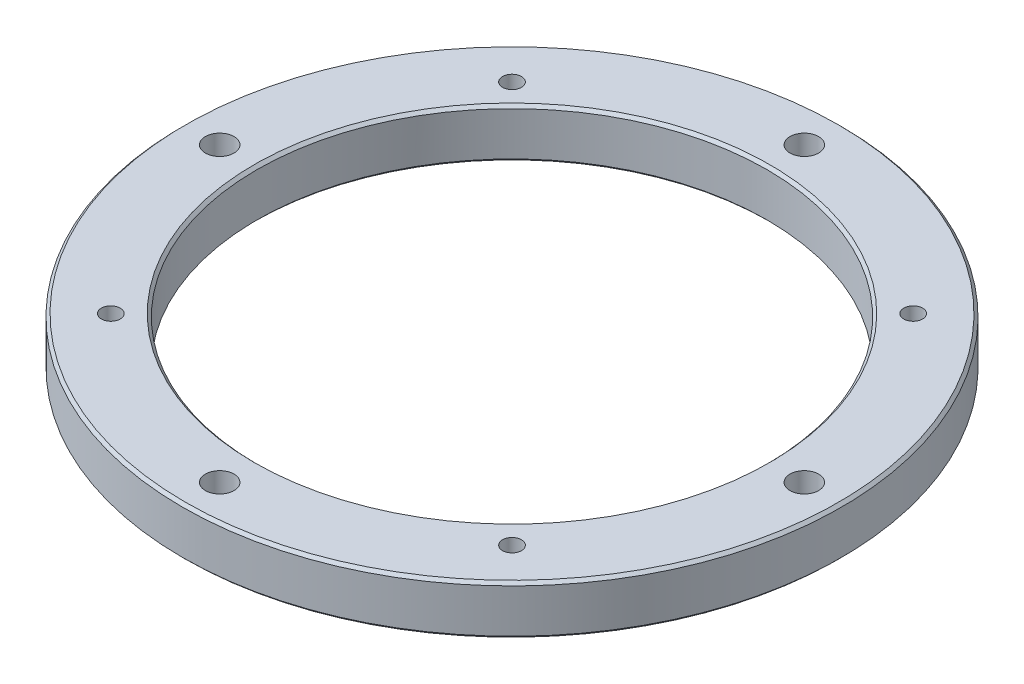
SolidWorks part; units mm, degrees
material "6061 合金"
ref_plane "正面" through (0, 0, 0) normal (0, 0, 1) x (1, 0, 0)
ref_plane "平面" through (0, 0, 0) normal (0, 1, 0) x (1, 0, 0)
ref_plane "右側面" through (0, 0, 0) normal (1, 0, 0) x (0, 0, -1)
sketch "ｽｹｯﾁ1" plane through (0, 0, 0) normal (0, 1, 0) x (1, 0, 0)
  circle A0 centre (0, 0) radius 57.5
  circle A1 centre (0, 0) radius 44.5
  dimension "D1" = 115
  dimension "D2" = 89
extrude "ﾎﾞｽ - 押し出し1" add sketch "ｽｹｯﾁ1" along normal blind 8.6
sketch "ｽｹｯﾁ2" plane through (0, 8.6, 0) normal (0, 1, 0) x (1, 0, 0)
  circle A0 centre (0, 0) radius 51 construction
  circle A1 centre (-51, 0) radius 2.5
  circle A2 centre (0, 51) radius 2.5
  circle A3 centre (51, 0) radius 2.5
  circle A4 centre (0, -51) radius 2.5
  point P14 (0, 0)
  dimension "D1" = 102
  dimension "D2" = 5
  dimension "D3" = 4
extrude "ｶｯﾄ - 押し出し1" cut sketch "ｽｹｯﾁ2" against normal through all
chamfer "面取り1" distance 0.5 angle 45 4 edges at (0, 8.6, 57.5) (0, 0, 57.5) (0, 0, 44.5) (0, 8.6, 44.5)
sketch "ｽｹｯﾁ3" plane through (0, 8.6, 0) normal (0, 1, 0) x (1, 0, 0)
  line L0 (0, 0) -> (0, -57) construction
  line L1 (0, 0) -> (-57, 0) construction
  circle A0 centre (0, 0) radius 57 construction
  circle A1 centre (-35, 35) radius 1.65
  circle A2 centre (-35, -35) radius 1.65
  circle A3 centre (35, -35) radius 1.65
  circle A4 centre (35, 35) radius 1.65
  dimension "D1" = 3.3
  dimension "D2" = 70
  dimension "D3" = 70
extrude "ｶｯﾄ - 押し出し2" cut sketch "ｽｹｯﾁ3" against normal through all
